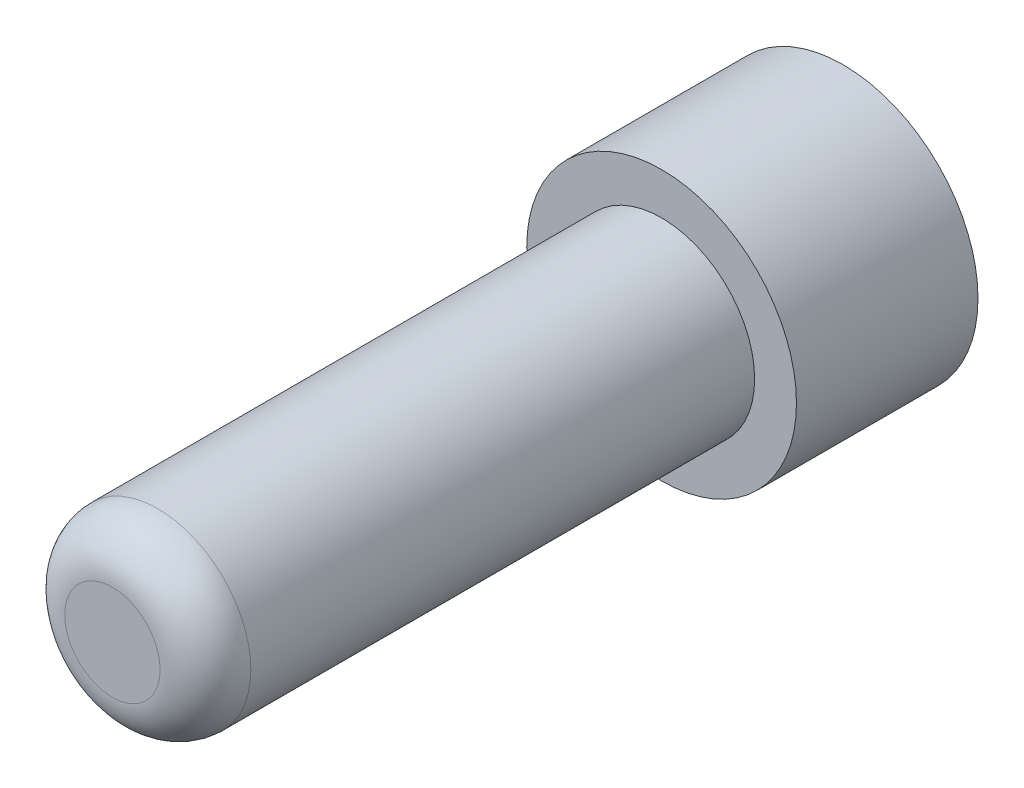
SolidWorks part; units mm, degrees
material "Alloy Steel"
ref_plane "Front Plane" through (0, 0, 0) normal (0, 0, 1) x (1, 0, 0)
ref_plane "Top Plane" through (0, 0, 0) normal (0, 1, 0) x (1, 0, 0)
ref_plane "Right Plane" through (0, 0, 0) normal (1, 0, 0) x (0, 0, -1)
sketch "Sketch1" plane through (0, 0, 0) normal (1, 0, 0) x (0, 0, -1)
  line L0 (-26.9906, 0) -> (26.9906, 0) construction
  line L1 (20.447, 0) -> (20.447, 7.5472)
  line L2 (20.447, 7.5472) -> (10.287, 7.5472)
  line L3 (10.287, 7.5472) -> (10.287, 5.207)
  line L4 (10.287, 5.207) -> (-20.447, 5.207)
  line L5 (-20.447, 5.207) -> (-20.447, 0)
  line L6 (20.447, 0) -> (-20.447, 0)
  point P4 (0, 0)
  dimension "D1" = 5.207
  dimension "D2" = 30.734
  dimension "D3" = 40.894
  dimension "D4" = 20.447
revolve "Revolve1" add sketch "Sketch1" angle 360 about L0
fillet "Fillet1" radius 2.54 1 edges at (5.207, 0, 20.447)
